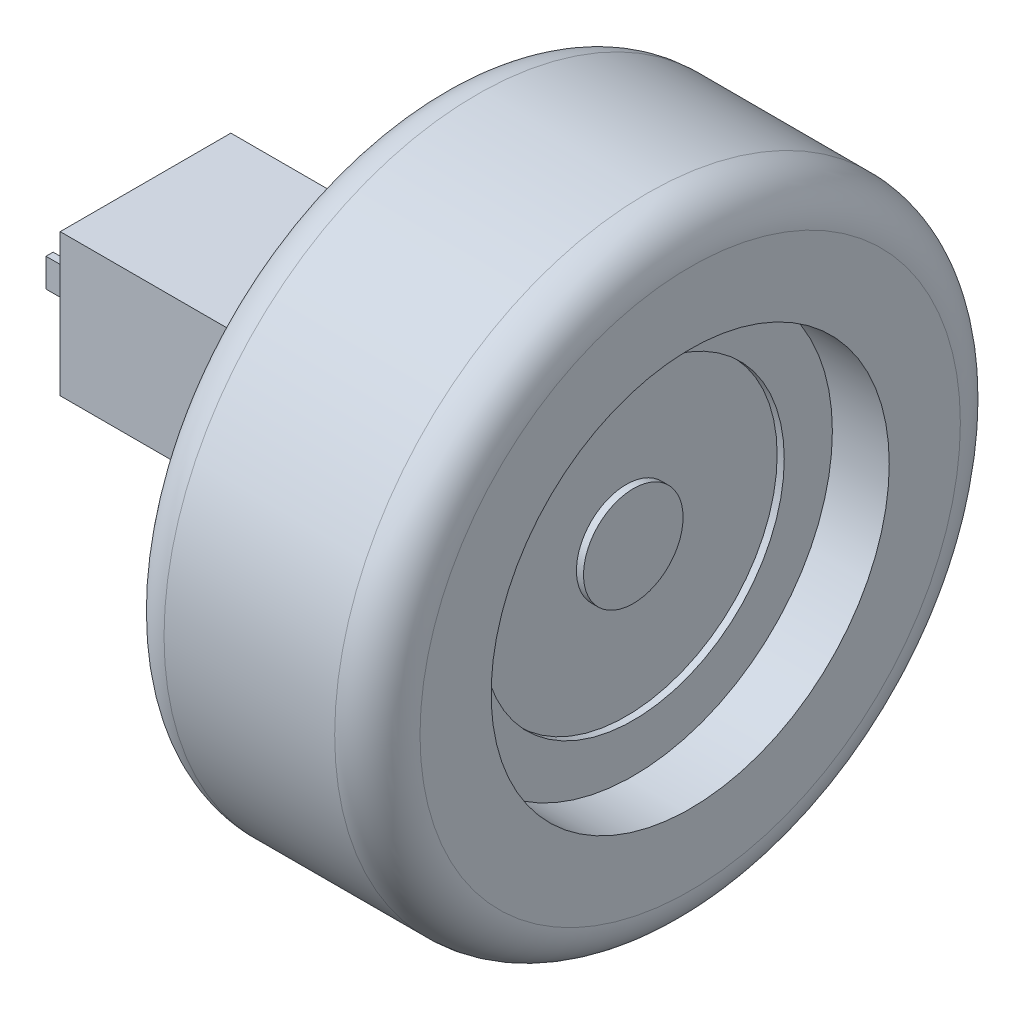
SolidWorks part; units mm, degrees
ref_plane "前视基准面" through (0, 0, 0) normal (0, 0, 1) x (1, 0, 0)
ref_plane "上视基准面" through (0, 0, 0) normal (0, 1, 0) x (1, 0, 0)
ref_plane "右视基准面" through (0, 0, 0) normal (1, 0, 0) x (0, 0, -1)
sketch "草图8" plane through (0, 0, 0) normal (1, 0, 0) x (0, 0, -1)
  line L1 (-6, 5) -> (6, 5)
  line L2 (-6, 5) -> (-6, -5)
  line L3 (-6, -5) -> (6, -5)
  line L4 (6, 5) -> (6, -5)
  line L5 (-6, 5) -> (6, -5) construction
  line L6 (-6, -5) -> (6, 5) construction
  point P0 (0, 0)
  dimension "D1" = 12
  dimension "D2" = 10
extrude "电机1" add sketch "草图8" along normal blind 24.3
sketch "草图10" plane through (24.3, 0, 0) normal (1, 0, 0) x (0, 0, -1)
  circle A0 centre (0, 0) radius 1.5
extrude "电机2" add sketch "草图10" along normal blind 5
sketch "草图11" plane through (24.3, 0, 0) normal (1, 0, 0) x (0, 0, -1)
  circle A0 centre (0.0371, 0) radius 2
extrude "电机3" add sketch "草图11" along normal blind 0.8
sketch "草图12" plane through (0, 0, 0) normal (-1, 0, 0) x (0, 0, 1)
  circle A0 centre (0, 0) radius 2.5
extrude "电机4" add sketch "草图12" along normal blind 1 contours A0
sketch "草图13" plane through (29.3, 0, 0) normal (1, 0, 0) x (0, 0, -1)
  circle A0 centre (0, 0) radius 22
extrude "轮子1" add sketch "草图13" along normal blind 9
sketch "草图15" plane through (38.3, 0, 0) normal (1, 0, 0) x (0, 0, -1)
  circle A0 centre (0, 0) radius 14
extrude "轮子3" cut sketch "草图15" against normal blind 4
sketch "草图16" plane through (29.3, 0, 0) normal (-1, 0, 0) x (0, 0, 1)
  circle A0 centre (0, 0) radius 14
  circle A1 centre (0, 0) radius 22
extrude "凸台-拉伸7" add sketch "草图16" along normal blind 9
sketch "草图17" plane through (0, 5, 0) normal (0, 1, 0) x (1, 0, 0)
  line L1 (0, 6) -> (16, 6)
  line L2 (0, 6) -> (0, -6)
  line L3 (0, -6) -> (16, -6)
  line L4 (0, 6) -> (0, -6)
  line L5 (0, -6) -> (24.3, -6)
  line L6 (24.3, -6) -> (24.3, 6)
  line L7 (24.3, 6) -> (0, 6)
  line L8 (0, 6) -> (0, -6)
  line L9 (0, -6) -> (24.3, -6)
  line L10 (24.3, -6) -> (24.3, 6)
  line L11 (24.3, 6) -> (0, 6)
  line L12 (16, 6) -> (16, -6)
  line L13 (24.3, 6) -> (18.3, 6)
  line L14 (24.3, 6) -> (24.3, -6)
  line L15 (24.3, -6) -> (18.3, -6)
  line L16 (18.3, 6) -> (18.3, -6)
  line M11 (0, -6) -> (24.3, -6)
  dimension "D2" = 16
  dimension "D3" = 6
  dimension "D1" = 0
extrude "切除-拉伸3" cut sketch "草图17" against normal blind 12 contours L16 L11 L12 M11
sketch "草图18" plane through (18.3, 0, 0) normal (-1, 0, 0) x (0, 0, 1)
  line L0 (6, 5) -> (-6, -5) construction
  line L1 (-6, 5) -> (6, 5) construction
  line L2 (6, 5) -> (6, -5) construction
  line L3 (6, -5) -> (-6, -5) construction
  line L4 (-6, -5) -> (-6, 5) construction
  circle A0 centre (0, 0) radius 1
  circle A1 centre (3.6, 3) radius 1.5
  circle A2 centre (-3.6, -3) radius 1.5
  circle A3 centre (-3.2, 2.2) radius 2.8
  dimension "D1" = 2
  dimension "D2" = 2
  dimension "D3" = 2
  dimension "D4" = 2.8
  dimension "D5" = 2.8
extrude "凸台-拉伸8" add sketch "草图18" along normal blind 3 contours A3 | A1 | A0 | A2
fillet "圆角1" radius 3 1 edges at (38.3, 0, -22)
fillet "圆角2" radius 3 1 edges at (20.3, 0, 22)
sketch "草图20" plane through (0, 0, 0) normal (-1, 0, 0) x (0, 0, 1)
  line L0 (-6, 0) -> (6, 0) construction
  line L1 (6, 5) -> (6, -5) construction
  line L3 (3.5, 1) -> (4, 1)
  line L4 (3.5, 1) -> (3.5, -1)
  line L5 (3.5, -1) -> (4, -1)
  line L6 (4, 1) -> (4, -1)
  line L7 (3.5, 1) -> (4, -1) construction
  line L8 (3.5, -1) -> (4, 1) construction
  line L9 (-4, 1) -> (-3.5, 1)
  line L10 (-4, 1) -> (-4, -1)
  line L11 (-4, -1) -> (-3.5, -1)
  line L12 (-3.5, 1) -> (-3.5, -1)
  line L13 (-4, 1) -> (-3.5, -1) construction
  line L14 (-4, -1) -> (-3.5, 1) construction
  point P0 (3.75, 0)
  point P6 (0, 0)
  point P12 (-3.75, 0)
  dimension "D1" = 0.5
  dimension "D2" = 2
  dimension "D3" = 3.5
  dimension "D4" = 0.5
  dimension "D5" = 2
  dimension "D6" = 3.5
extrude "凸台-拉伸9" add sketch "草图20" along normal blind 3
sketch "草图21" plane through (34.3, 0, 0) normal (1, 0, 0) x (0, 0, -1)
  circle A0 centre (0, 0) radius 3.5
  circle A1 centre (0, 0) radius 10.6171
extrude "切除-拉伸5" cut sketch "草图21" against normal blind 0.5
